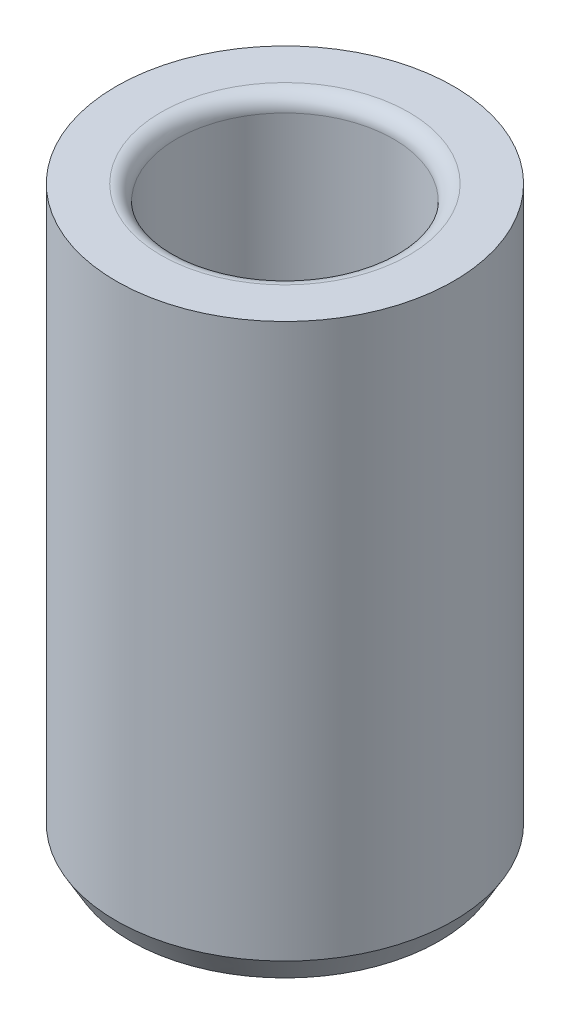
SolidWorks part; units mm, degrees
material "TOOL STEEL"
ref_plane "Front Plane" through (0, 0, 0) normal (0, 0, 1) x (1, 0, 0)
ref_plane "Top Plane" through (0, 0, 0) normal (0, 1, 0) x (1, 0, 0)
ref_plane "Right Plane" through (0, 0, 0) normal (1, 0, 0) x (0, 0, -1)
sketch "Sketch1" plane through (0, 0, 0) normal (0, 0, 1) x (1, 0, 0)
  line L0 (0, 0) -> (0, -19.05) construction
  line L1 (4.0799, 0) -> (5.5562, 0)
  line L2 (3.5719, -0.508) -> (3.5719, -18.669)
  line L3 (3.9529, -19.05) -> (5.5563, -19.05)
  line L4 (5.5562, 0) -> (5.5563, -19.05)
  line L5 (3.5719, -18.669) -> (3.9529, -19.05)
  arc A0 (4.0799, 0) -> (3.5719, -0.508) centre (4.0799, -0.508) ccw
  point P2 (3.5719, -19.05)
  dimension "D1" = 0.508
  dimension "L" = 19.05
  dimension "ID" = 7.1437
  dimension "OD" = 11.1125
revolve "BODY" add sketch "Sketch1" angle 360 about L0
chamfer "Chamfer1" distance 0.8128 angle 30 1 edges at (-5.5562, -19.05, 0)
sketch "Sketch2" plane through (0, 0, 0) normal (0, 1, 0) x (1, 0, 0)
  line L0 (0, -3.5719) -> (0, -2.8099) construction
  line L1 (-4.7934, -2.8099) -> (4.7934, -2.8099)
  line L2 (-4.7934, -2.8099) -> (-4.7934, -5.5562)
  line L3 (-4.7934, -5.5562) -> (4.7934, -5.5562)
  line L4 (4.7934, -2.8099) -> (4.7934, -5.5562)
  circle A0 centre (0, 0) radius 5.5562 construction
  circle A1 centre (0, 0) radius 3.5719 construction
  dimension "D2" = 0.762
extrude "Flat Cut" [suppressed] cut sketch "Sketch2" against normal blind 3.175
